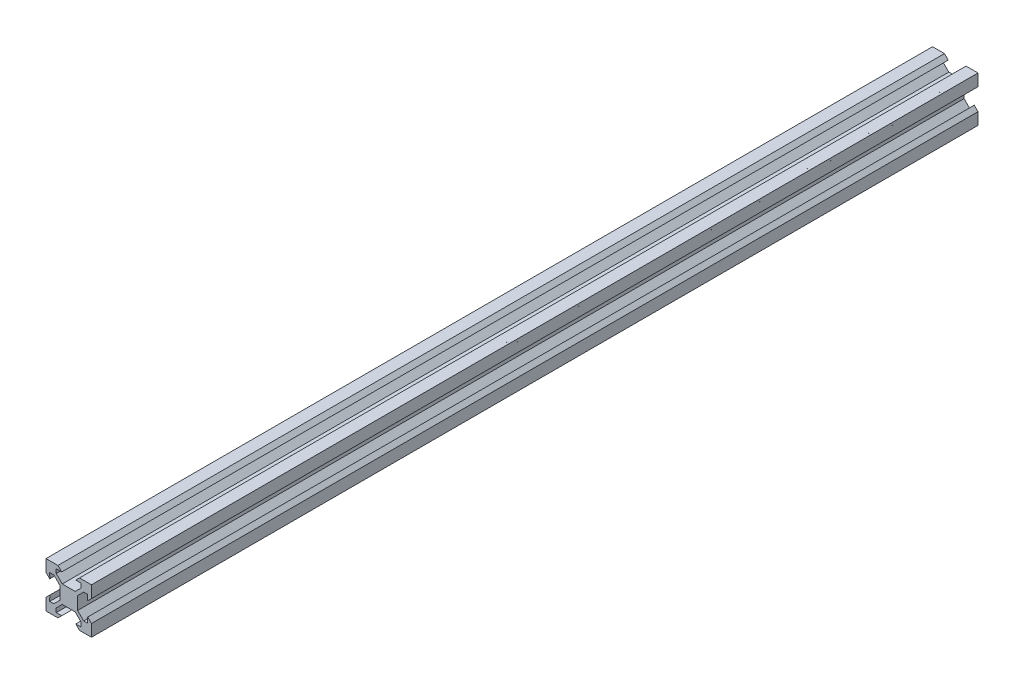
SolidWorks part; units mm, degrees
ref_plane "Front Plane" through (0, 0, 0) normal (0, 0, 1) x (1, 0, 0)
ref_plane "Top Plane" through (0, 0, 0) normal (0, 1, 0) x (1, 0, 0)
ref_plane "Right Plane" through (0, 0, 0) normal (1, 0, 0) x (0, 0, -1)
sketch "Sketch1" plane through (0, 0, 0) normal (0, 0, 1) x (1, 0, 0)
  line L88 (2.8343, 3.894) -> (-2.8343, 3.894)
  line L89 (-2.8343, 3.894) -> (-5.5, 6.5588)
  line L90 (-5.5, 6.5588) -> (-5.5, 8.3491)
  line L91 (-5.5, 8.3491) -> (-3.1, 8.3491)
  line L92 (-3.1, 8.3491) -> (-4.75, 9.9986)
  line L93 (-4.75, 9.9986) -> (-10, 9.9986)
  line L94 (-10, 9.9986) -> (-10, 4.747)
  line L95 (-10, 4.747) -> (-8.35, 3.0975)
  line L96 (-8.35, 3.0975) -> (-8.3507, 5.4975)
  line L97 (-8.3507, 5.4975) -> (-6.5605, 5.498)
  line L98 (-6.5605, 5.498) -> (-3.8948, 2.8332)
  line L99 (-3.8948, 2.8332) -> (-3.8948, -2.8332)
  line L100 (-3.8948, -2.8332) -> (-6.5605, -5.498)
  line L101 (-6.5605, -5.498) -> (-8.3507, -5.4975)
  line L102 (-8.3507, -5.4975) -> (-8.35, -3.0975)
  line L103 (-8.35, -3.0975) -> (-10, -4.747)
  line L104 (-10, -4.747) -> (-10, -9.9986)
  line L105 (-10, -9.9986) -> (-4.75, -9.9986)
  line L106 (-4.75, -9.9986) -> (-3.1, -8.3491)
  line L107 (-3.1, -8.3491) -> (-5.5, -8.3491)
  line L108 (-5.5, -8.3491) -> (-5.5, -6.5588)
  line L109 (-5.5, -6.5588) -> (-2.8343, -3.894)
  line L110 (-2.8343, -3.894) -> (2.8343, -3.894)
  line L111 (2.8343, -3.894) -> (5.5, -6.5588)
  line L112 (5.5, -6.5588) -> (5.5, -8.3491)
  line L113 (5.5, -8.3491) -> (3.1, -8.3491)
  line L114 (3.1, -8.3491) -> (4.75, -9.9986)
  line L115 (4.75, -9.9986) -> (10, -9.9986)
  line L116 (10, -9.9986) -> (10, -4.747)
  line L117 (10, -4.747) -> (8.35, -3.0975)
  line L118 (8.35, -3.0975) -> (8.3507, -5.4975)
  line L119 (8.3507, -5.4975) -> (6.5605, -5.498)
  line L120 (6.5605, -5.498) -> (3.8948, -2.8332)
  line L121 (3.8948, -2.8332) -> (3.8948, 2.8332)
  line L122 (3.8948, 2.8332) -> (6.5605, 5.498)
  line L123 (6.5605, 5.498) -> (8.3507, 5.4975)
  line L124 (8.3507, 5.4975) -> (8.35, 3.0975)
  line L125 (8.35, 3.0975) -> (10, 4.747)
  line L126 (10, 4.747) -> (10, 9.9986)
  line L127 (10, 9.9986) -> (4.75, 9.9986)
  line L128 (4.75, 9.9986) -> (3.1, 8.3491)
  line L129 (3.1, 8.3491) -> (5.5, 8.3491)
  line L130 (5.5, 8.3491) -> (5.5, 6.5588)
  line L131 (5.5, 6.5588) -> (2.8343, 3.894)
  dimension "D2" = 5.25
  dimension "D3" = 19.9971
  dimension "D4" = 20
extrude "Boss-Extrude1" add sketch "Sketch1" along normal blind 390
